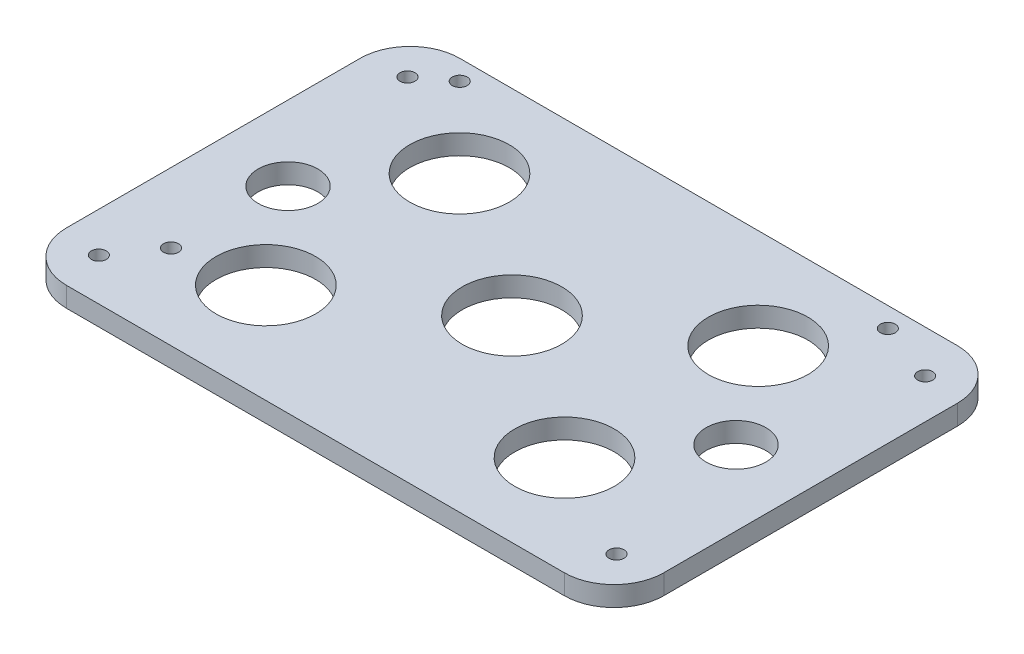
SolidWorks part; units mm, degrees
ref_plane "Front Plane" through (0, 0, 0) normal (0, 0, 1) x (1, 0, 0)
ref_plane "Top Plane" through (0, 0, 0) normal (0, 1, 0) x (1, 0, 0)
ref_plane "Right Plane" through (0, 0, 0) normal (1, 0, 0) x (0, 0, -1)
sketch "Sketch1" plane through (0, 0, 0) normal (0, 1, 0) x (1, 0, 0)
  line L0 (-50, -39.5) -> (50, -39.5)
  line L1 (60, -29.5) -> (60, 29.5)
  line L2 (50, 39.5) -> (-50, 39.5)
  line L3 (-60, 29.5) -> (-60, -29.5)
  circle A0 centre (40, 35.5) radius 1.5
  arc A1 (50, -39.5) -> (60, -29.5) centre (50, -29.5) ccw
  arc A2 (60, 29.5) -> (50, 39.5) centre (50, 29.5) ccw
  arc A3 (-50, 39.5) -> (-60, 29.5) centre (-50, 29.5) ccw
  arc A4 (-60, -29.5) -> (-50, -39.5) centre (-50, -29.5) ccw
  circle A5 centre (45, 0) radius 6
  circle A6 centre (30, 19.45) radius 10
  circle A7 centre (30, -19.45) radius 10
  circle A8 centre (0, 0) radius 10
  circle A9 centre (-30, -19.45) radius 10
  circle A10 centre (-46, 35.5) radius 1.5
  circle A11 centre (-46, -22.5) radius 1.5
  circle A12 centre (-45, 0) radius 6
  circle A13 centre (-30, 19.45) radius 10
extrude "Boss-Extrude1" add sketch "Sketch1" along normal blind 4
sketch "Sketch2" plane through (0, 4, 0) normal (0, 1, 0) x (1, 0, 0)
  line L1 (52, -31) -> (-52, -31)
  line L2 (52, -31) -> (52, 31)
  line L3 (52, 31) -> (-52, 31)
  line L4 (-52, -31) -> (-52, 31)
  line L5 (52, -31) -> (-52, 31) construction
  line L6 (52, 31) -> (-52, -31) construction
  circle A0 centre (-52, 31) radius 1.5
  circle A1 centre (52, 31) radius 1.5
  circle A2 centre (52, -31) radius 1.5
  circle A3 centre (-52, -31) radius 1.5
  point P0 (0, 0)
  dimension "D1" = 62
  dimension "D2" = 104
extrude "Cut-Extrude1" cut sketch "Sketch2" against normal blind 25 contours L3 A0 L4 | L4 A0 L3 | L4 A3 L1 | L1 A3 L4 | L1 A2 L2 | L2 A2 L1 | L2 A1 L3 | L3 A1 L2
